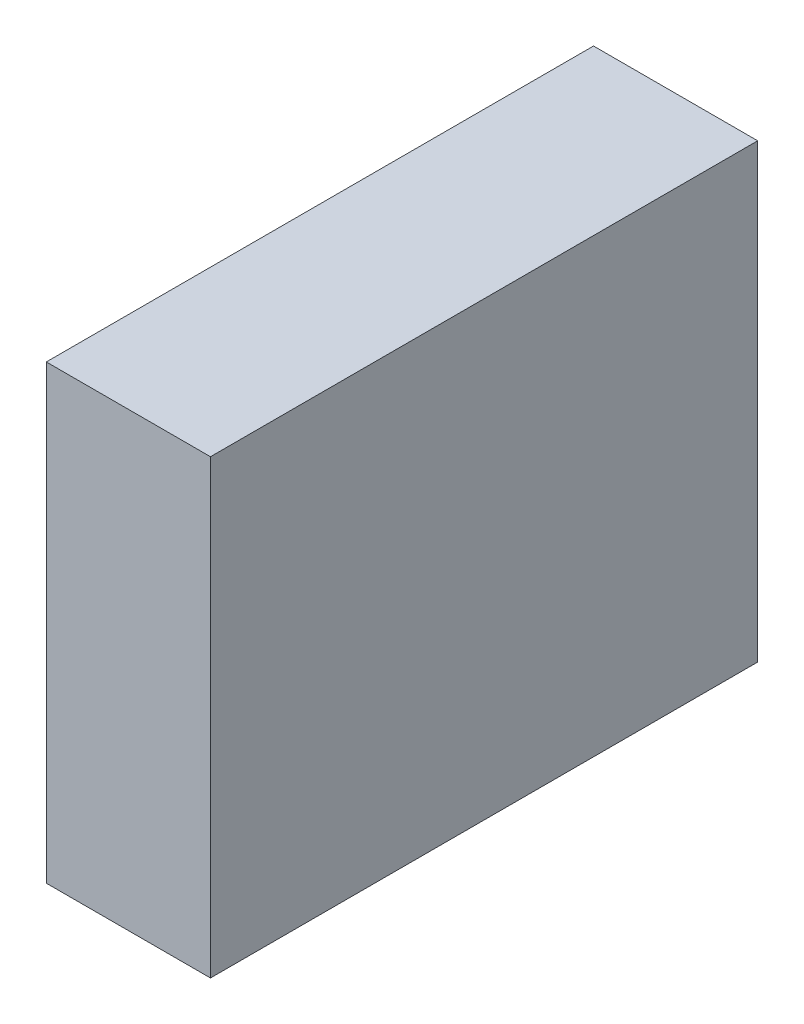
SolidWorks part; units mm, degrees
material "6061 Alloy"
ref_plane "Front Plane" through (0, 0, 0) normal (0, 0, 1) x (1, 0, 0)
ref_plane "Top Plane" through (0, 0, 0) normal (0, 1, 0) x (1, 0, 0)
ref_plane "Right Plane" through (0, 0, 0) normal (1, 0, 0) x (0, 0, -1)
sketch "Sketch1" plane through (0, 0, 0) normal (0, 1, 0) x (1, 0, 0)
  line L1 (0, 0) -> (38.1, 0)
  line L2 (0, 0) -> (0, 127)
  line L3 (0, 127) -> (38.1, 127)
  line L4 (38.1, 0) -> (38.1, 127)
  dimension "D1" = 127
  dimension "D2" = 38.1
extrude "Boss-Extrude1" add sketch "Sketch1" along normal blind 104.775
